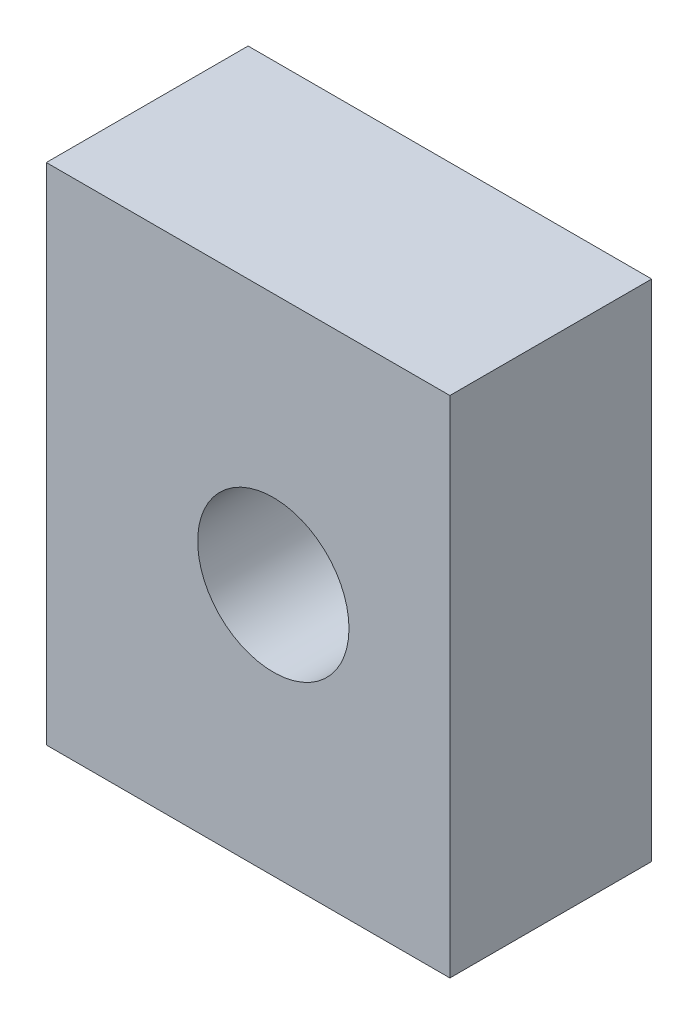
SolidWorks part; units mm, degrees
ref_plane "Front Plane" through (0, 0, 0) normal (0, 0, 1) x (1, 0, 0)
ref_plane "Top Plane" through (0, 0, 0) normal (0, 1, 0) x (1, 0, 0)
ref_plane "Right Plane" through (0, 0, 0) normal (1, 0, 0) x (0, 0, -1)
sketch "Sketch1" plane through (0, 0, 0) normal (0, 0, 1) x (1, 0, 0)
  line L0 (0, 10) -> (8, 10)
  line L1 (8, 0) -> (0, 0)
  line L2 (0, 10) -> (0, 0)
  line L3 (8, 10) -> (8, 0)
  circle A0 centre (4.5, 5) radius 1.5
  dimension "D3" = 8
  dimension "D1" = 3
  dimension "D2" = 4.5
  dimension "D4" = 5
  dimension "D5" = 10
extrude "Boss-Extrude1" add sketch "Sketch1" along normal blind 4
